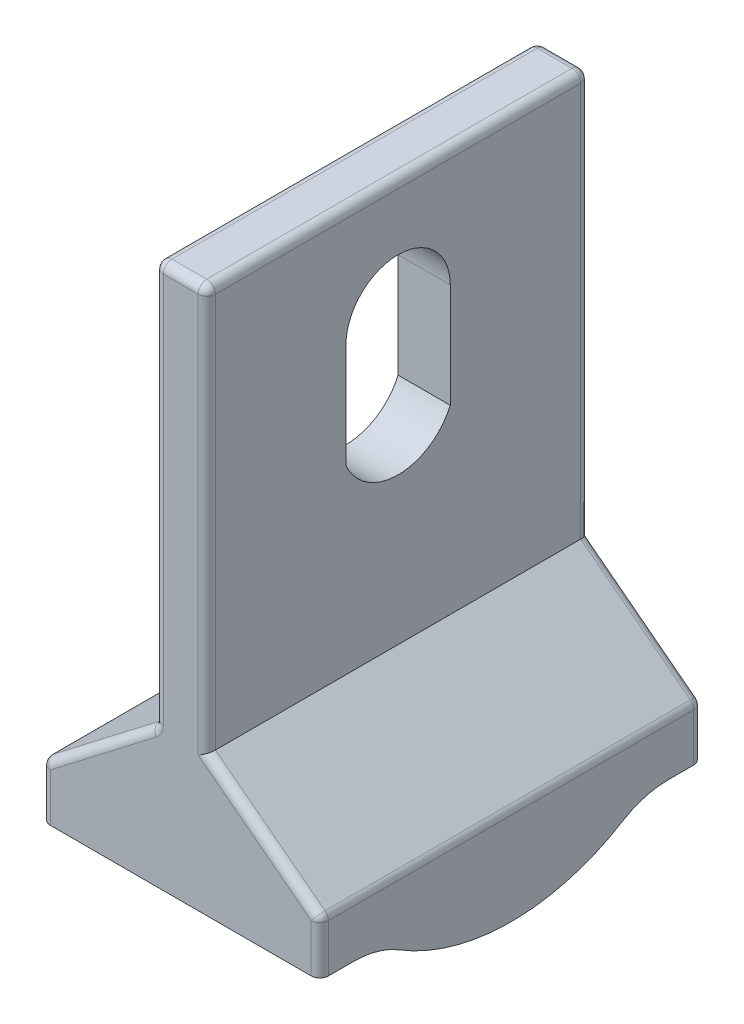
SolidWorks part; units mm, degrees
ref_plane "Plano frontal" through (0, 0, 0) normal (0, 0, 1) x (1, 0, 0)
ref_plane "Plano superior" through (0, 0, 0) normal (0, 1, 0) x (1, 0, 0)
ref_plane "Plano direito" through (0, 0, 0) normal (1, 0, 0) x (0, 0, -1)
sketch "Esboço2" plane through (0, 0, 0) normal (0, 0, 1) x (1, 0, 0)
  line L0 (0, 0) -> (0, 34.6668) construction
  line L1 (-1.5, 34.6668) -> (1.5, 34.6668)
  line L2 (1.5, 34.6668) -> (1.5, 11.4668)
  line L3 (1.5, 11.4668) -> (8, 6.4668)
  line L4 (8, 6.4668) -> (8, 3.4668)
  line L5 (8, 3.4668) -> (-8, 3.4668)
  line L6 (-8, 6.4668) -> (-8, 3.4668)
  line L7 (-1.5, 11.4668) -> (-8, 6.4668)
  line L8 (-1.5, 34.6668) -> (-1.5, 11.4668)
  point P10 (0, 3.4668)
  dimension "D1" = 3
  dimension "D2" = 16
  dimension "D3" = 3
  dimension "D4" = 8
  dimension "D5" = 31.2
extrude "Ressalto-extrusão1" add sketch "Esboço2" along normal blind 22
sketch "Esboço3" plane through (8, 0, 0) normal (1, 0, 0) x (0, 0, -1)
  line L0 (-11, 3.4668) -> (-11, 9.1951) construction
  line L1 (-22, 3.4668) -> (0, 3.4668) construction
  line L2 (-11, 3.4668) -> (-18.5, 3.4668) construction
  line L3 (-11, 3.4668) -> (-3.5, 3.4668) construction
  line L4 (-11, 3.4668) -> (-11, 1.4668) construction
  line L9 (0, 3.4668) -> (0, 6.4668)
  line L10 (0, 6.4668) -> (-22, 6.4668)
  line L11 (-22, 6.4668) -> (-22, 3.4668)
  line L12 (-22, 3.4668) -> (0, 3.4668)
  line L16 (-18.5, 3.4668) -> (-3.5, 3.4668)
  arc A0 (-18.5, 3.4668) -> (-3.5, 3.4668) centre (-11, 13.2051) ccw
  dimension "D1" = 7.5
  dimension "D2" = 7.5
  dimension "D3" = 2
  dimension "D4" = 0
extrude "Ressalto-extrusão2" add sketch "Esboço3" against normal blind 16
fillet "Filete1" radius 5 2 edges at (0, 3.4668, 18.5) (0, 3.4668, 3.5)
fillet "Filete2" radius 0.5 18 edges at (-4.75, 8.9668, 0) (4.75, 8.9668, 0) (-8, 4.9668, 0) (8, 4.9668, 0) (-1.5, 11.4668, 11) (-1.5, 23.0668, 0) (0, 34.6668, 0) (0, 34.6668, 22) (-1.5, 34.6668, 11) (1.5, 34.6668, 11) (1.5, 23.0668, 0) (8, 6.4668, 11) (8, 4.9668, 22) (-8, 4.9668, 22) (-4.75, 8.9668, 22) (-1.5, 23.0668, 22) (1.5, 23.0668, 22) (4.75, 8.9668, 22)
fillet "Filete3" radius 0.5 3 edges at (-7.8536, 6.3947, 21.8536) (-7.8536, 6.3947, 0.1464) (-8, 6.4668, 11)
sketch "Esboço4" plane through (1.5, 0, 0) normal (1, 0, 0) x (0, 0, -1)
  line L0 (-11, 34.6668) -> (-11, 24.6668) construction
  line L1 (-21.5, 34.6668) -> (-0.5, 34.6668) construction
  line L2 (-13.25, 24.6668) -> (-8.75, 24.6668) construction
  line L3 (-14, 27.8853) -> (-14, 21.8853)
  line L4 (-8, 27.8853) -> (-8, 21.8853)
  arc A0 (-14, 27.8853) -> (-8, 27.8853) centre (-11, 27.8853) cw
  arc A1 (-14, 21.8853) -> (-8, 21.8853) centre (-11, 23.1908) ccw
  dimension "D2" = 3
  dimension "D1" = 10
  dimension "D3" = 6
extrude "Corte-extrusão1" cut sketch "Esboço4" against normal through all
